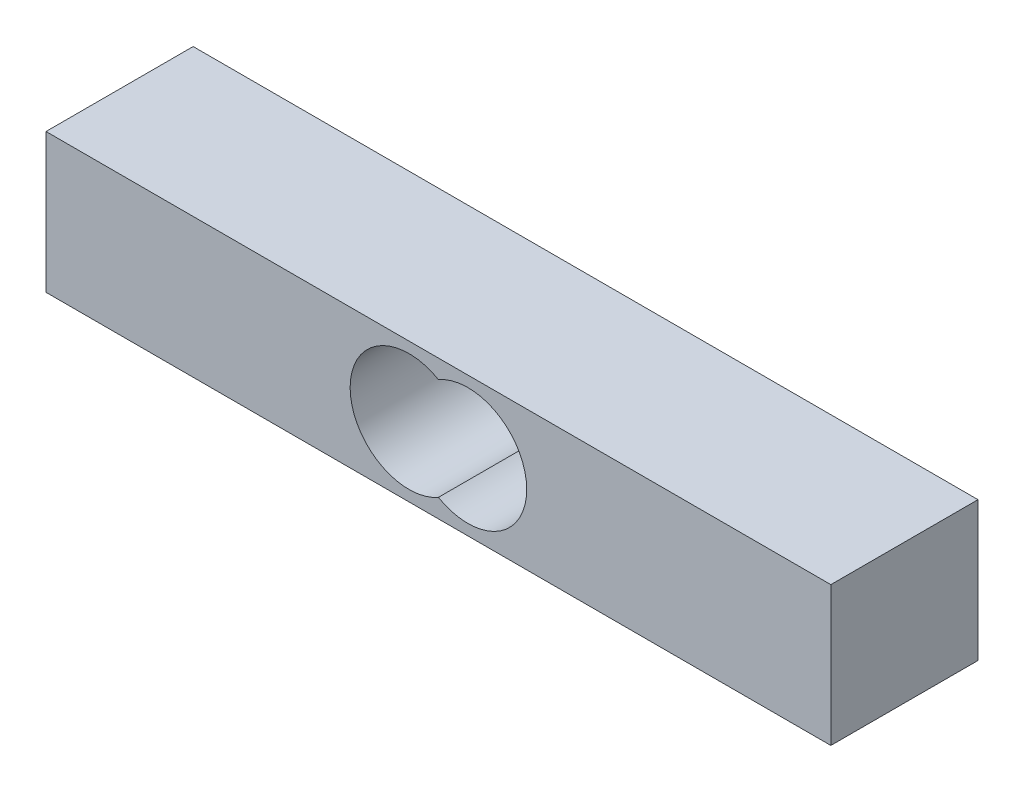
SolidWorks part; units mm, degrees
ref_plane "Front Plane" through (0, 0, 0) normal (0, 0, 1) x (1, 0, 0)
ref_plane "Top Plane" through (0, 0, 0) normal (0, 1, 0) x (1, 0, 0)
ref_plane "Right Plane" through (0, 0, 0) normal (1, 0, 0) x (0, 0, -1)
sketch "Sketch1" plane through (0, 0, 0) normal (0, 1, 0) x (1, 0, 0)
  line L1 (-40, -7.5) -> (40, -7.5)
  line L2 (-40, -7.5) -> (-40, 7.5)
  line L3 (-40, 7.5) -> (40, 7.5)
  line L4 (40, -7.5) -> (40, 7.5)
  line L5 (-40, -7.5) -> (40, 7.5) construction
  line L6 (-40, 7.5) -> (40, -7.5) construction
  point P0 (0, 0)
  dimension "D1" = 80
  dimension "D2" = 15
extrude "Boss-Extrude1" add sketch "Sketch1" along normal blind 14.2
sketch "Sketch4" plane through (0, 0, 7.5) normal (0, 0, 1) x (1, 0, 0)
  line L1 (0, 0) -> (0, 14.2) construction
  line L2 (-40, 14.2) -> (40, 14.2) construction
  arc A0 (0, 1.9038) -> (0, 12.2962) centre (3, 7.1) ccw
  arc A1 (0, 12.2962) -> (0, 1.9038) centre (-3, 7.1) ccw
  point P2 (0, 0)
  point P5 (3, 7.6443)
  point P6 (0, 7.1)
  dimension "D2" = 12
  dimension "D1" = 3
extrude "Cut-Extrude1" cut sketch "Sketch4" against normal through all contours A0 A1
equation "\"e\"= 3"
equation "\"D1@Sketch4\"=\"e\""
equation "\"d\"= 12"
equation "\"D2@Sketch4\"=\"d\""
